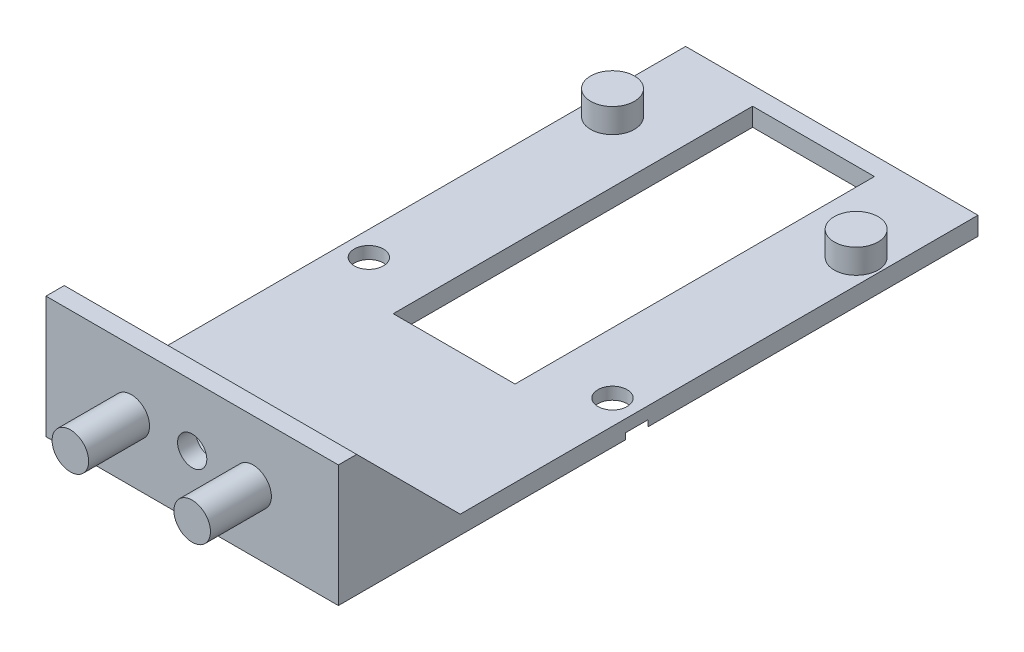
SolidWorks part; units mm, degrees
material "ABS"
ref_plane "Plan de face" through (0, 0, 0) normal (0, 0, 1) x (1, 0, 0)
ref_plane "Plan de dessus" through (0, 0, 0) normal (0, 1, 0) x (1, 0, 0)
ref_plane "Plan de droite" through (0, 0, 0) normal (1, 0, 0) x (0, 0, -1)
sketch "Esquisse1" plane through (0, 0, 0) normal (0, 1, 0) x (1, 0, 0)
  line L1 (-12, -19) -> (12, -19)
  line L2 (-12, -19) -> (-12, 19)
  line L3 (-12, 19) -> (12, 19)
  line L4 (12, -19) -> (12, 19)
  line L5 (-12, -19) -> (12, 19) construction
  line L6 (-12, 19) -> (12, -19) construction
  line L11 (-5, -12) -> (5, -12)
  line L12 (0, 2.75) -> (0, 0) construction
  line L13 (-5, -12) -> (-5, 17.5)
  line L14 (-5, 17.5) -> (5, 17.5)
  line L15 (5, -12) -> (5, 17.5)
  line L16 (-5, -12) -> (5, 17.5) construction
  line L17 (-5, 17.5) -> (5, -12) construction
  point P0 (0, 0)
  dimension "D1" = 24
  dimension "D2" = 38
  dimension "D3" = 1.5
  dimension "D4" = 7
  dimension "D5" = 7
extrude "Shape" add sketch "Esquisse1" along normal blind 1.5
sketch "Esquisse2" plane through (0, 1.5, 0) normal (0, 1, 0) x (1, 0, 0)
  line L0 (10, 19) -> (10, -19) construction
  line L1 (12, 19) -> (-12, 19) construction
  line L2 (-12, -19) -> (12, -19) construction
  line L3 (10, -19) -> (0, -19) construction
  circle A0 centre (10, -9) radius 1.2
  dimension "D2" = 2.4
  dimension "D1" = 10
  dimension "D3" = 10
extrude "VisHoles" cut sketch "Esquisse2" against normal blind 1.5
sketch "Esquisse3" plane through (0, 1.5, 0) normal (0, 1, 0) x (1, 0, 0)
  line L0 (12, 21) -> (-12, 21) construction
  line L1 (12, -19) -> (12, 19) construction
  line L2 (-12, 19) -> (-12, -19) construction
  line L3 (-12, -19) -> (12, -19) construction
  line L4 (0, 21) -> (0, -19) construction
  line L5 (10, -9) -> (10, 1) construction
  line L6 (0, 1) -> (10, 1) construction
  line L7 (10, 1) -> (10, 21) construction
  circle A0 centre (10, 11) radius 1.8
  line M6 (12, -19) -> (12, 19)
  dimension "D2" = 3.6
  dimension "D1" = 40
extrude "Lockers" add sketch "Esquisse3" along normal blind 2 contours A0 M6
sketch "Esquisse4" plane through (0, 0, 0) normal (0, 1, 0) x (1, 0, 0)
  circle A0 centre (10, -9) radius 2.2
  dimension "D1" = 4.4
extrude "ScrewHatRemover" cut sketch "Esquisse4" along normal blind 0.5
mirror "Symétrie1" about plane through (0, 0, 0) normal (1, 0, 0) of "ScrewHatRemover", "VisHoles", "Lockers"
sketch "Esquisse6" plane through (0, 0, 0) normal (0, -1, 0) x (1, 0, 0)
  line L0 (10, -11) -> (-10, -11) construction
  line L1 (12, 19) -> (-12, 19)
  line L2 (12, 19) -> (12, 33.5)
  line L3 (12, 33.5) -> (-12, 33.5)
  line L4 (-12, 19) -> (-12, 33.5)
  dimension "D1" = 44.5
extrude "Rallonge" add sketch "Esquisse6" against normal up to surface (1.5 mm away) up to face at (-10, 1.5, -9.2)
sketch "Esquisse7" plane through (0, 1.5, 0) normal (0, 1, 0) x (1, 0, 0)
  line L0 (-12, 19) -> (-12, -33.5) construction
  line L1 (12, -33.5) -> (-12, -33.5)
  line L2 (12, -33.5) -> (12, -32)
  line L3 (12, -32) -> (-12, -32)
  line L4 (-12, -33.5) -> (-12, -32)
  dimension "D1" = 1.5
extrude "Boss.-Extru.2" add sketch "Esquisse7" along normal blind 8.5
sketch "Esquisse8" plane through (0, 0, 33.5) normal (0, 0, 1) x (1, 0, 0)
  line L0 (0, 0) -> (0, 10) construction
  line L1 (-12, 10) -> (12, 10) construction
  circle A0 centre (0, 5) radius 1.2
  dimension "D1" = 2.4
extrude "Enlèv. mat.-Extru.1" cut sketch "Esquisse8" against normal blind 10
sketch "Esquisse9" plane through (0, 0, 33.5) normal (0, 0, 1) x (1, 0, 0)
  line L0 (0, 5) -> (5, 5) construction
  line L1 (0, 5) -> (-5, 5) construction
  circle A0 centre (5, 5) radius 1.5
  circle A1 centre (-5, 5) radius 1.5
  dimension "D1" = 3
  dimension "D2" = 5
extrude "Boss.-Extru.3" add sketch "Esquisse9" along normal blind 5
sketch "Esquisse12" plane through (-12, 0, 0) normal (-1, 0, 0) x (0, 0, 1)
  line L0 (32, 10) -> (23.5, 1.5)
  line L1 (-19, 1.5) -> (32, 1.5) construction
  line L2 (32, 10) -> (32, 1.5) construction
  dimension "D1" = 45
rib "Nervure11" sketch "Esquisse12" sketch "Esquisse12" thickness 1 extrusion direction parallel to sketch draft on no parameters "D1"=1
mirror "Symétrie2" about plane through (0, 0, 0) normal (1, 0, 0) of "Nervure11"
equation "\"entretoiseBearing\"= 1.5mm"
equation "\"length_tibia\"= 206mm"
equation "\"length_femur\"= 117mm"
equation "\"length_coxa\"= 27mm"
equation "\"height\"= 40mm"
equation "\"width\"= 100mm"
equation "\"lever\"= 40mm"
equation "\"errorFlat\"= 0.20mm"
equation "\"errorFlat_tight\"= 0.15mm"
equation "\"errorCircle\"= 0.40mm"
equation "\"errorCircle_tight\" = 0.30mm"
equation "\"cuticule\"=1.5mm"
equation "\"cuticule_attach_w\"=10mm"
equation "\"cuticule_attach_h\"=2.5mm"
equation "\"depthMagnet\"= 1mm"
equation "\"insert_d\" = 3.2mm"
equation "\"insert_l\" = 5mm"
equation "\"D2@Esquisse2\"= 2.00mm + \"errorCircle\""
equation "\"D2@Esquisse3\"= 4 - \"errorCircle\""
equation "\"D1@Esquisse4\"=4 + \"errorCircle\""
equation "\"D1@Esquisse7\"= \"cuticule\""
equation "\"D1@Boss.-Extru.2\"= 10 - \"cuticule\""
equation "\"D1@Esquisse8\"= 2 + \"errorCircle\""
